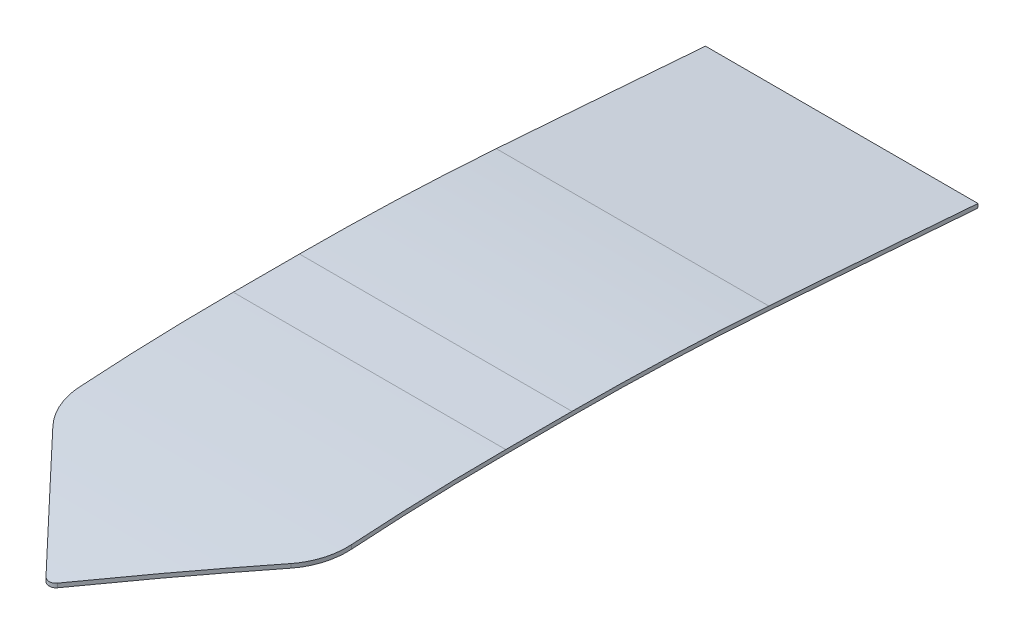
SolidWorks part; units mm, degrees
ref_plane "Front Plane" through (0, 0, 0) normal (0, 0, 1) x (1, 0, 0)
ref_plane "Top Plane" through (0, 0, 0) normal (0, 1, 0) x (1, 0, 0)
ref_plane "Right Plane" through (0, 0, 0) normal (1, 0, 0) x (0, 0, -1)
sketch "Sketch1" plane through (221.2232, 2174.8893, 3089.3536) normal (1, 0, 0) x (0, 0, -1)
  line L1 (20.32, -469.9) -> (0, -469.9) construction
  line L4 (20.32, -469.9) -> (0, -469.9) construction
  line L36 (418.4703, 343.8483) -> (835.7994, 343.8483) construction
  line L37 (418.4703, 343.8483) -> (835.7994, 343.8483)
  line L40 (418.4703, 318.4483) -> (835.7994, 318.4483)
  line L41 (-1603.5297, 202.4836) -> (-1599.9954, 177.3306)
  line L42 (3395.4703, 198.9533) -> (3393.4944, 173.6302)
  arc A0 (2076.5794, 298.5837) -> (1699.8995, 321.9101) centre (835.7994, -16684.7351) ccw construction
  arc A2 (1699.8995, 321.9101) -> (1433.1995, 333.366) centre (835.7994, -16684.7351) ccw construction
  arc A6 (1433.1995, 333.366) -> (835.7994, 343.8483) centre (835.7994, -16684.7351) ccw construction
  arc A7 (2076.5794, 298.5837) -> (1699.8995, 321.9101) centre (835.7994, -16684.7351) ccw
  arc A8 (1699.8995, 321.9101) -> (1433.1995, 333.366) centre (835.7994, -16684.7351) ccw
  arc A9 (1433.1995, 333.366) -> (835.7994, 343.8483) centre (835.7994, -16684.7351) ccw
  arc A10 (418.4703, 343.8483) -> (-1603.5297, 202.4836) centre (418.4703, -14187.6006) ccw
  arc A11 (2076.5794, 298.5837) -> (3395.4703, 198.9533) centre (-17442.8336, -266875.6126) cw
  arc A12 (2074.7287, 273.2512) -> (3393.4944, 173.6302) centre (-17442.8336, -266875.6126) cw
  arc A13 (2074.7287, 273.2512) -> (1698.6106, 296.5429) centre (835.7994, -16684.7351) ccw
  arc A14 (1698.6106, 296.5429) -> (1432.3084, 307.9816) centre (835.7994, -16684.7351) ccw
  arc A15 (1432.3084, 307.9816) -> (835.7994, 318.4483) centre (835.7994, -16684.7351) ccw
  arc A16 (418.4703, 318.4483) -> (-1599.9954, 177.3306) centre (418.4703, -14187.6006) ccw
  dimension "D2" = 4999
  dimension "D1" = 2022
  dimension "D4" = 14531.4488
  dimension "D5" = 267886.2793
  dimension "D6" = 17028.5833
  dimension "D7" = 17028.5833
  dimension "D8" = 417.3291
  dimension "D3" = 1318.8908
  dimension "D10" = 1658.1092
  dimension "D9" = 25.4
extrude "Boss-Extrude1" add sketch "Sketch1" along normal blind 1562 and the other way blind 176
sketch "Sketch2" plane through (0, 0, 0) normal (0, 1, 0) x (1, 0, 0)
  line L0 (950.6024, -4674.1843) -> (1664.2567, -3917.291)
  line L1 (914.2232, 306.1166) -> (914.2232, -7016.6759) construction
  line L2 (45.2232, 306.1166) -> (1783.2232, 306.1166) construction
  line L5 (1773.2232, -3801.7223) -> (55.2232, -3801.7223) construction
  line L8 (1773.2232, -3642.8834) -> (1773.2232, 306.1166)
  line L9 (1773.2232, 306.1166) -> (55.2232, 306.1166)
  line L10 (55.2232, 306.1166) -> (55.2232, -3642.8834)
  line L12 (2470.299, 1079.7144) -> (-893.2768, 1079.7144)
  line L13 (2470.299, 1079.7144) -> (2470.299, -4890.7405)
  line L14 (2470.299, -4890.7405) -> (-893.2768, -4890.7405)
  line L15 (-893.2768, 1079.7144) -> (-893.2768, -4890.7405)
  line L16 (45.2232, 306.1166) -> (1783.2232, 306.1166) construction
  line L17 (164.1897, -3917.291) -> (877.844, -4674.1843)
  line L18 (55.2232, -3642.8834) -> (1773.2232, -3642.8834) construction
  line L19 (45.2232, -4692.8834) -> (1783.2232, -4692.8834) construction
  arc A3 (950.6024, -4674.1843) -> (877.844, -4674.1843) centre (914.2232, -4639.8834) cw
  arc A4 (1664.2567, -3917.291) -> (1773.2232, -3642.8834) centre (1373.2232, -3642.8834) ccw
  arc A5 (55.2232, -3642.8834) -> (164.1897, -3917.291) centre (455.2232, -3642.8834) ccw
  point P21 (914.2232, 306.1166)
  dimension "D1" = 50
  dimension "D3" = 400
  dimension "D2" = 1718
  dimension "D4" = 997
  dimension "D5" = 1050
  dimension "D6" = 4999
extrude "Cut-Extrude2" cut sketch "Sketch2" along normal blind 6472
ref_plane "Plane1" through (914.2232, 0, 0) normal (1, 0, 0) x (0, 0, -1)
